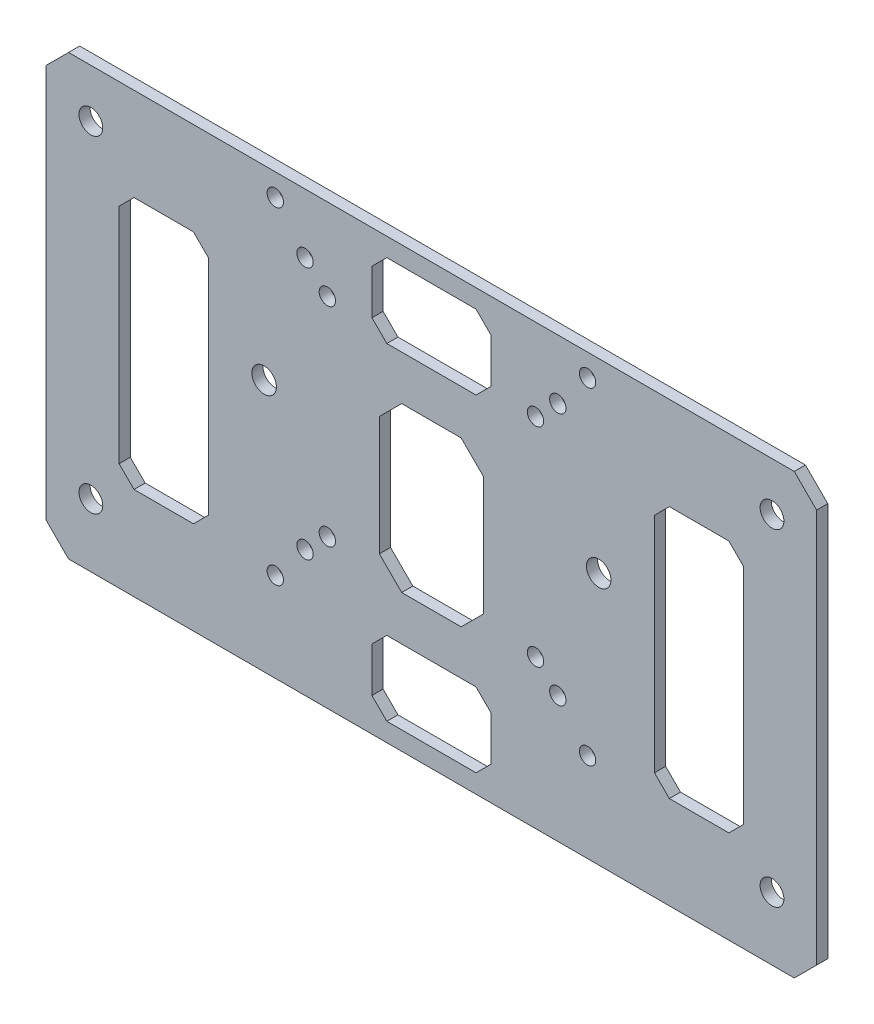
SolidWorks part; units mm, degrees
material "碳纤维板_1600kg_m3"
ref_plane "前视基准面" through (0, 0, 0) normal (0, 0, 1) x (1, 0, 0)
ref_plane "上视基准面" through (0, 0, 0) normal (0, 1, 0) x (1, 0, 0)
ref_plane "右视基准面" through (0, 0, 0) normal (1, 0, 0) x (0, 0, -1)
other "Configuration Table"
sketch "草图1" plane through (0, 0, 0) normal (0, 0, 1) x (1, 0, 0)
  line L64 (-48.804, -9) -> (48.804, -9)
  line L65 (48.804, -9) -> (51.804, -6)
  line L66 (51.804, -6) -> (51.804, 47)
  line L67 (51.804, 47) -> (48.804, 50)
  line L68 (48.804, 50) -> (-48.804, 50)
  line L69 (-48.804, 50) -> (-51.804, 47)
  line L70 (-51.804, 47) -> (-51.804, -6)
  line L71 (-51.804, -6) -> (-48.804, -9)
  line L112 (-4, 9.5) -> (4, 9.5)
  line L113 (4, 9.5) -> (7, 12.5)
  line L114 (7, 12.5) -> (7, 28.5)
  line L115 (7, 28.5) -> (4, 31.5)
  line L116 (4, 31.5) -> (-4, 31.5)
  line L117 (-4, 31.5) -> (-7, 28.5)
  line L118 (-7, 28.5) -> (-7, 12.5)
  line L119 (-7, 12.5) -> (-4, 9.5)
  line L120 (-40, 3.5) -> (-32, 3.5)
  line L121 (-32, 3.5) -> (-30, 5.5)
  line L122 (-30, 5.5) -> (-30, 35.5)
  line L123 (-30, 35.5) -> (-32, 37.5)
  line L124 (-32, 37.5) -> (-40, 37.5)
  line L125 (-40, 37.5) -> (-42, 35.5)
  line L126 (-42, 35.5) -> (-42, 5.5)
  line L127 (-42, 5.5) -> (-40, 3.5)
  line L128 (32, 3.5) -> (40, 3.5)
  line L129 (40, 3.5) -> (42, 5.5)
  line L130 (42, 5.5) -> (42, 35.5)
  line L131 (42, 35.5) -> (40, 37.5)
  line L132 (40, 37.5) -> (32, 37.5)
  line L133 (32, 37.5) -> (30, 35.5)
  line L134 (30, 35.5) -> (30, 5.5)
  line L135 (30, 5.5) -> (32, 3.5)
  line L136 (-6, -6.5) -> (6, -6.5)
  line L137 (6, -6.5) -> (8, -4.5)
  line L138 (8, -4.5) -> (8, 1.5)
  line L139 (8, 1.5) -> (6, 3.5)
  line L140 (6, 3.5) -> (-6, 3.5)
  line L141 (-6, 3.5) -> (-8, 1.5)
  line L142 (-8, 1.5) -> (-8, -4.5)
  line L143 (-8, -4.5) -> (-6, -6.5)
  line L144 (-6, 37.5) -> (6, 37.5)
  line L145 (6, 37.5) -> (8, 39.5)
  line L146 (8, 39.5) -> (8, 45.5)
  line L147 (8, 45.5) -> (6, 47.5)
  line L148 (6, 47.5) -> (-6, 47.5)
  line L149 (-6, 47.5) -> (-8, 45.5)
  line L150 (-8, 45.5) -> (-8, 39.5)
  line L151 (-8, 39.5) -> (-6, 37.5)
  circle A24 centre (-45.804, -0.5) radius 1.6
  circle A25 centre (-45.804, 43.5) radius 1.6
  circle A26 centre (45.804, -0.5) radius 1.6
  circle A27 centre (45.804, 43.5) radius 1.6
  circle A28 centre (-21, 3) radius 1.1
  circle A29 centre (21, 3) radius 1.1
  circle A30 centre (-14, 11) radius 1.1
  circle A31 centre (-14, 39) radius 1.1
  circle A32 centre (14, 11) radius 1.1
  circle A33 centre (14, 39) radius 1.1
  circle A34 centre (-17, 8) radius 1.1
  circle A35 centre (-17, 42) radius 1.1
  circle A36 centre (17, 8) radius 1.1
  circle A37 centre (17, 42) radius 1.1
  circle A38 centre (-22.5, 25) radius 1.65
  circle A39 centre (22.5, 25) radius 1.65
extrude "1p5mm竖向开孔板_上下四孔" add sketch "草图1" along normal blind 1.5
sketch "草图2" plane through (0, 0, 0) normal (0, 0, 1) x (1, 0, 0)
  circle A0 centre (-21, 47) radius 1.1
  circle A1 centre (21, 47) radius 1.1
extrude "上沿电池板钢索孔_D2p2" cut sketch "草图2" along normal blind 1.5
